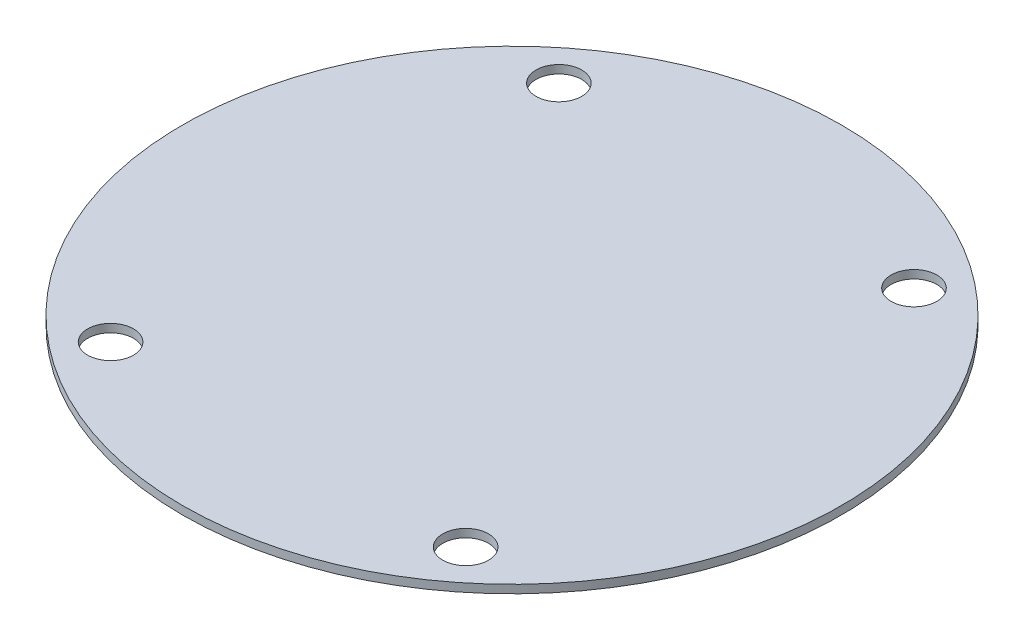
SolidWorks part; units mm, degrees
ref_plane "Front Plane" through (0, 0, 0) normal (0, 0, 1) x (1, 0, 0)
ref_plane "Top Plane" through (0, 0, 0) normal (0, 1, 0) x (1, 0, 0)
ref_plane "Right Plane" through (0, 0, 0) normal (1, 0, 0) x (0, 0, -1)
sketch "Sketch1" plane through (0, 0, 0) normal (0, 1, 0) x (1, 0, 0)
  circle A0 centre (0, 0) radius 40
  dimension "D1" = 80
extrude "Boss-Extrude1" add sketch "Sketch1" along normal blind 1
sketch "Sketch2" plane through (0, 0, 0) normal (0, -1, 0) x (-1, 0, 0)
  circle A2 centre (21.55, -27.1742) radius 2.775
  circle A3 centre (-21.55, -27.1742) radius 2.775
  circle A4 centre (21.55, 27.2409) radius 2.775
  circle A5 centre (-21.55, 27.2409) radius 2.775
  dimension "D5" = 5.55
  dimension "D6" = 5.55
  dimension "D10" = 5.55
  dimension "D11" = 5.55
extrude "Cut-Extrude4" cut sketch "Sketch2" against normal through all
